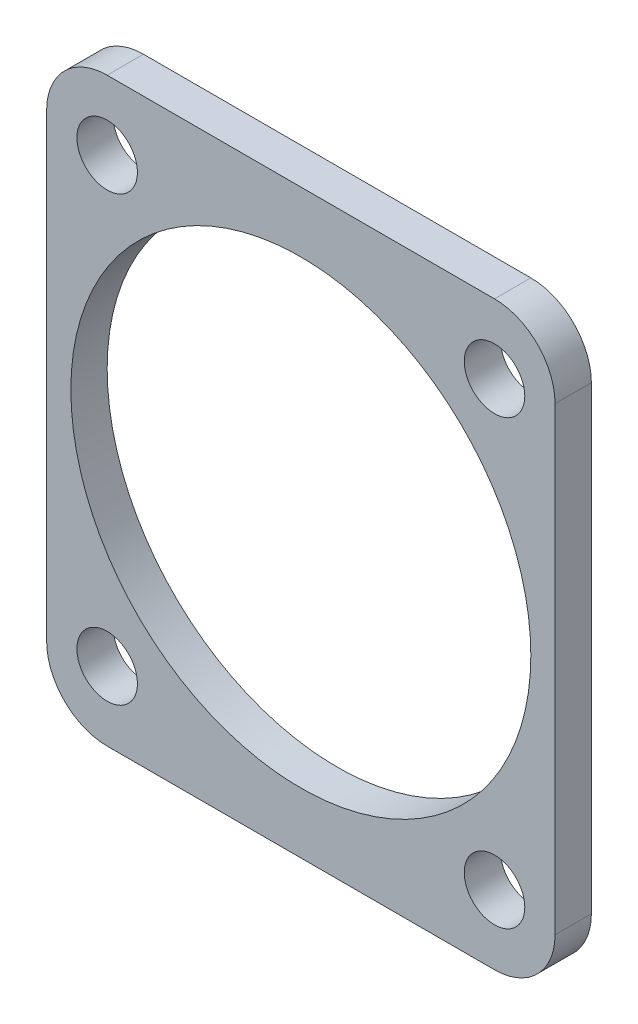
SolidWorks part; units mm, degrees
ref_plane "Front Plane" through (0, 0, 0) normal (0, 0, 1) x (1, 0, 0)
ref_plane "Top Plane" through (0, 0, 0) normal (0, 1, 0) x (1, 0, 0)
ref_plane "Right Plane" through (0, 0, 0) normal (1, 0, 0) x (0, 0, -1)
sketch "Sketch1" plane through (0, 0, 0) normal (0, 0, 1) x (1, 0, 0)
  line L1 (-21, -24) -> (21, -24)
  line L2 (-21, -24) -> (-21, 24)
  line L3 (-21, 24) -> (21, 24)
  line L4 (21, -24) -> (21, 24)
  line L5 (-21, -24) -> (21, 24) construction
  line L6 (-21, 24) -> (21, -24) construction
  circle A0 centre (0, 0) radius 19
  circle A1 centre (-16, 18.2857) radius 2.5
  circle A2 centre (16, 18.2857) radius 2.5
  circle A3 centre (16, -18.2857) radius 2.5
  circle A4 centre (-16, -18.2857) radius 2.5
  point P0 (0, 0)
  point P16 (-15.1636, 17.3298)
  dimension "D1" = 5
  dimension "D5" = 38
  dimension "D2" = 5
  dimension "D3" = 48
  dimension "D4" = 42
extrude "Boss-Extrude1" add sketch "Sketch1" along normal blind 3
fillet "Fillet1" radius 5 4 edges at (21, -24, 1.5) (-21, -24, 1.5) (-21, 24, 1.5) (21, 24, 1.5)
